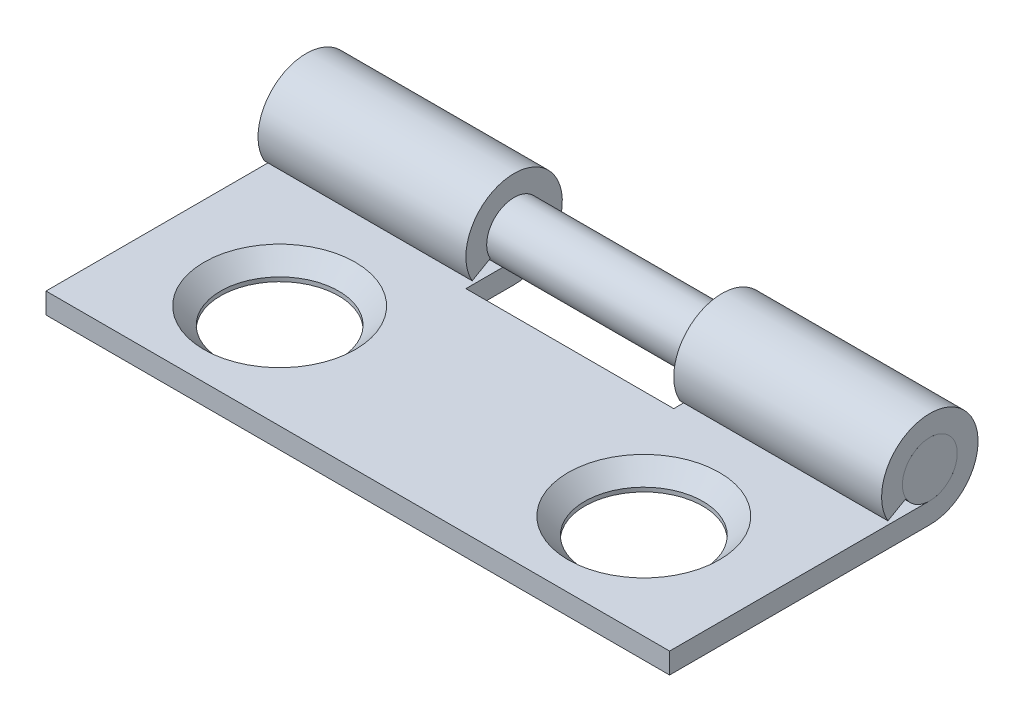
SolidWorks part; units mm, degrees
ref_plane "Front Plane" through (0, 0, 0) normal (0, 0, 1) x (1, 0, 0)
ref_plane "Top Plane" through (0, 0, 0) normal (0, 1, 0) x (1, 0, 0)
ref_plane "Right Plane" through (0, 0, 0) normal (1, 0, 0) x (0, 0, -1)
sketch "Sketch1" plane through (0, 0, 0) normal (0, 1, 0) x (1, 0, 0)
  line L0 (-9.525, 0) -> (9.525, 0) construction
  line L1 (-9.525, -7.9502) -> (-9.525, 7.9502) construction
  line L2 (-9.525, -7.9502) -> (-5.5626, -7.9502) construction
  line L3 (5.5626, -4.7752) -> (-5.5626, -4.7752) construction
  line L4 (-5.5626, -7.9502) -> (5.5626, -7.9502) construction
  line L5 (9.525, -7.9502) -> (9.525, -4.7752) construction
  line L6 (5.5626, -7.9502) -> (9.525, -7.9502) construction
  line L7 (-9.525, 7.9502) -> (-4.7498, 7.9502) construction
  line L8 (-4.7498, 7.9502) -> (11.1252, 7.9502) construction
  line L9 (11.1252, 7.9502) -> (27.0002, 7.9502) construction
  line L10 (27.0002, 7.9502) -> (30.9626, 7.9502) construction
  line L11 (5.5626, -7.0866) -> (5.5626, -2.4638) construction
  line L12 (5.5626, -4.7752) -> (9.525, -4.7752) construction
  line L13 (-5.5626, -4.7752) -> (-5.5626, -7.9502) construction
  line L14 (5.5626, 4.7752) -> (-5.5626, 4.7752) construction
  point P3 (5.5626, -6.5786)
  point P4 (0, 0)
  point P8 (-9.525, 0)
  point P17 (-3.175, 0)
  point P21 (5.5626, -4.7752)
  dimension "Frame Leaf Height" = 19.05
  dimension "Overall Width" = 15.9004
  dimension "Hole to End 1" = 3.9624
  dimension "Hole to End 2" = 3.9624
  dimension "D1" = 3.9624
  dimension "D2" = 4.7752
  dimension "D4" = 15.875
  dimension "D6" = 15.875
  dimension "Knuckle Length" = 6.35
  dimension "Hole Chamfer Dia" = 4.6228
  dimension "Hole Center to Pin" = 4.7752
  dimension "Door Leaf Height" = 19.05
  dimension "Mounting Hole Diameter" = 3.6068
  dimension "D3" = 11.1252
  dimension "Frame Leaf Width" = 7.9502
  dimension "Door Leaf Width" = 7.9502
sketch "Sketch2" plane through (0, 0, 0) normal (1, 0, 0) x (0, 0, -1)
  line L2 (0, -1.4732) -> (0, -0.8382) construction
  line L4 (0, 0.8382) -> (0, -0.8382) construction
  point P8 (0, 0)
  dimension "Leaf Thickness" = 0.635
  dimension "Pin Diameter" = 1.6764
sketch "Sketch3" plane through (0, 0, 0) normal (1, 0, 0) x (0, 0, -1)
  line L3 (0, 0) -> (-1.4732, -0.8382) construction
  line L4 (0, -1.4732) -> (-7.9502, -1.4732)
  line L5 (-7.9502, -1.4732) -> (-7.9502, -0.8382)
  line L7 (-7.9502, -0.8382) -> (0, -0.8382)
  line L8 (-7.9502, 0) -> (7.9502, 0) construction
  line L9 (-0.7285, -0.4145) -> (-1.2805, -0.7285)
  line L11 (-1.4732, 0) -> (-1.4732, -0.8382) construction
  circle A4 centre (0, 0) radius 0.8382 construction
  circle A5 centre (0, 0) radius 1.4732 construction
  arc A8 (-0.7285, -0.4145) -> (0, -0.8382) centre (0, 0) cw
  arc A9 (-1.2805, -0.7285) -> (0, -1.4732) centre (0, 0) cw
  point P0 (-1.2805, -0.7285)
  point P13 (-0.7285, -0.4145)
extrude "Boss-Extrude1" add sketch "Sketch3" along normal mid plane 19.05
pattern_circular "CirPattern1" [suppressed] count 2 over 360 about axis through (0, 0.8382, 0) along (0, -1, 0)
sketch "Sketch4" plane through (0, 0, 0) normal (0, 1, 0) x (1, 0, 0)
  line L0 (-9.525, -1.4732) -> (9.525, -1.4732) construction
  line L1 (-9.525, -1.4732) -> (9.525, -1.4732) construction
  line L2 (9.525, 1.4732) -> (-9.525, 1.4732) construction
  line L3 (9.525, 1.4732) -> (-9.525, 1.4732) construction
  line L4 (-3.175, -1.4732) -> (-3.175, 1.4732)
  line L6 (-3.175, 1.4732) -> (3.175, 1.4732)
  line L7 (3.175, -1.4732) -> (-3.175, -1.4732)
  line L8 (3.175, 1.4732) -> (3.175, -1.4732)
  point P8 (-3.175, 0)
  dimension "D1" = 6.35
extrude "Cut-Extrude1" cut sketch "Sketch4" against normal through all both and the other way through all
sketch "Sketch10" [suppressed] plane through (0, 0, 0) normal (0, 1, 0) x (1, 0, 0)
  line L0 (9.525, 1.4732) -> (-9.525, 1.4732) construction
  line L5 (-3.1623, 1.4732) -> (-9.525, 1.4732)
  line L6 (-3.1623, 1.4732) -> (-3.1623, -1.4732)
  line L7 (-3.1623, -1.4732) -> (-9.525, -1.4732)
  line L8 (-9.525, 1.4732) -> (-9.525, -1.4732)
  line L9 (3.1623, 1.4732) -> (9.525, 1.4732)
  line L10 (3.1623, 1.4732) -> (3.1623, -1.4732)
  line L11 (3.1623, -1.4732) -> (9.525, -1.4732)
  line L12 (9.525, 1.4732) -> (9.525, -1.4732)
  dimension "D1" = 0.0127
extrude "Cut-Extrude4" [suppressed] cut sketch "Sketch10" against normal through all both and the other way through all
sketch "Sketch5" plane through (0, -0.8382, 0) normal (0, 1, 0) x (1, 0, 0)
  line L0 (5.5626, -4.7752) -> (-5.5626, -4.7752) construction
  line L1 (0, -4.7752) -> (0, -7.9502) construction
  line L2 (-5.5626, -4.7752) -> (-5.5626, -7.9502) construction
  line L3 (9.525, -7.9502) -> (-9.525, -7.9502) construction
  circle A0 centre (5.5626, -4.7752) radius 2.3114
  circle A2 centre (-5.5626, -4.7752) radius 2.3114
extrude "Cut-Extrude2" cut sketch "Sketch5" against normal through all draft 45
sketch "Sketch9" plane through (0, 0, 0) normal (0, 1, 0) x (1, 0, 0)
  circle A0 centre (5.5626, -4.7752) radius 1.8034
  circle A2 centre (-5.5626, -4.7752) radius 1.8034
  dimension "D1" = 3.6068
extrude "Cut-Extrude3" cut sketch "Sketch9" against normal through all both and the other way through all
sketch "Sketch11" [suppressed] plane through (0, -0.8382, 0) normal (0, 1, 0) x (1, 0, 0)
  circle A0 centre (5.5626, 4.7752) radius 2.3114
  circle A1 centre (-5.5626, 4.7752) radius 2.3114
  circle A2 centre (-5.5626, -4.7752) radius 2.3114 construction
sketch "Sketch6" plane through (0, 0, 0) normal (1, 0, 0) x (0, 0, -1)
  circle A0 centre (0, 0) radius 0.8382
  dimension "D1" = 1.6764
extrude "Boss-Extrude2" add sketch "Sketch6" along normal mid plane 19.05 separate body
sketch "Sketch7" [suppressed] plane through (0, 0, 0) normal (1, 0, 0) x (0, 0, -1)
  line L0 (-0.8382, 0) -> (0.8382, 0) construction
  line L1 (-7.9502, 0) -> (7.9502, 0) construction
  line L2 (7.9502, -0.8382) -> (7.9502, -1.4732) construction
  line L3 (7.9502, -0.8382) -> (7.9502, -1.4732) construction
  line L4 (7.9502, -1.4732) -> (-7.9502, -1.4732) construction
  line L5 (-7.9502, -1.4732) -> (-7.9502, -0.8382)
  point P6 (0, 0)
  point P8 (0.8382, 0)
  point P9 (-0.8382, 0)
  point P12 (7.9502, -0.8382)
  point P13 (7.9502, -1.4732)
  point P14 (-7.9502, -1.4732)
  dimension "D1" = 1.6764
  dimension "D2" = 15.9004
  dimension "D3" = 0.635
sketch "Sketch8" [suppressed] plane through (0, 0, 0) normal (0, 1, 0) x (1, 0, 0)
  line L0 (-7.874, -4.7752) -> (-3.2512, -4.7752) construction
  line L1 (5.5626, 4.7752) -> (-5.5626, 4.7752) construction
  line L2 (3.2512, -4.7752) -> (7.874, -4.7752) construction
  line L3 (-5.5626, -2.4638) -> (-5.5626, -7.0866) construction
  line L5 (5.5626, -2.4638) -> (5.5626, -7.0866) construction
  line L6 (-5.5626, 7.0866) -> (-5.5626, 2.4638) construction
  line L7 (-7.874, 4.7752) -> (-3.2512, 4.7752) construction
  line L10 (5.5626, 7.0866) -> (5.5626, 2.4638) construction
  line L11 (3.2512, 4.7752) -> (7.874, 4.7752) construction
  line L12 (5.5626, 4.7752) -> (7.197, 6.4096) construction
  circle A1 centre (-5.5626, -4.7752) radius 2.3114 construction
  circle A3 centre (5.5626, -4.7752) radius 2.3114 construction
  circle A7 centre (5.5626, 4.7752) radius 2.3114 construction
  circle A8 centre (-5.5626, 4.7752) radius 2.3114 construction
  circle A9 centre (5.5626, 4.7752) radius 2.3114 construction
  point P2 (-9.525, 0)
  point P7 (-5.5626, -4.7752)
  point P19 (5.5626, -4.7752)
  point P25 (-9.525, 7.9502)
  point P26 (30.9626, 7.9502)
  point P28 (-9.525, -7.9502)
  point P30 (9.525, -7.9502)
  point P32 (-7.874, -4.7752)
  point P33 (-5.5626, -2.4638)
  point P34 (-3.2512, -4.7752)
  point P35 (-5.5626, -7.0866)
  point P40 (7.874, -4.7752)
  point P41 (5.5626, -7.0866)
  point P42 (3.2512, -4.7752)
  point P43 (5.5626, -2.4638)
  point P67 (5.5626, -7.9502)
  point P69 (-5.5626, -7.9502)
  point P71 (-4.7498, 7.9502)
  point P73 (-5.5626, 4.7752)
  point P76 (5.5626, 4.7752)
  point P77 (27.0002, 7.9502)
  point P78 (11.1252, 7.9502)
  point P82 (-5.5626, 7.0866)
  point P83 (-7.874, 4.7752)
  point P84 (-5.5626, 2.4638)
  point P85 (-3.2512, 4.7752)
  point P90 (5.5626, 2.4638)
  point P91 (3.2512, 4.7752)
  point P92 (5.5626, 7.0866)
  point P97 (7.197, 6.4096)
  dimension "D1" = 45
equation "\"D1@Sketch1\"=\"Hole to End 1@Sketch1\""
equation "\"D6@Sketch1\"=\"D4@Sketch1\""
equation "\"D1@Boss-Extrude1\" = \"Frame Leaf Height@Sketch1\""
equation "\"D1@Sketch4\"=\"Knuckle Length@Sketch1\""
equation "\"D1@Sketch6\"=\"Pin Diameter@Sketch2\""
equation "\"D1@Boss-Extrude2\" = \"Frame Leaf Height@Sketch1\""
equation "\"D1@Sketch7\"=\"Pin Diameter@Sketch2\""
equation "\"D2@Sketch7\"=\"Overall Width@Sketch1\""
equation "\"D3@Sketch7\"=\"Leaf Thickness@Sketch2\""
equation "\"Knuckle Length@Sketch1\"=\"Frame Leaf Height@Sketch1\" / 3"
equation "\"Hole to End 2@Sketch1\"=\"Hole to End 1@Sketch1\""
equation "\"D1@Sketch9\"=\"Mounting Hole Diameter@Sketch1\""
equation "\"Hole Chamfer Dia@Sketch1\"=\"Mounting Hole Diameter@Sketch1\"+.04"
